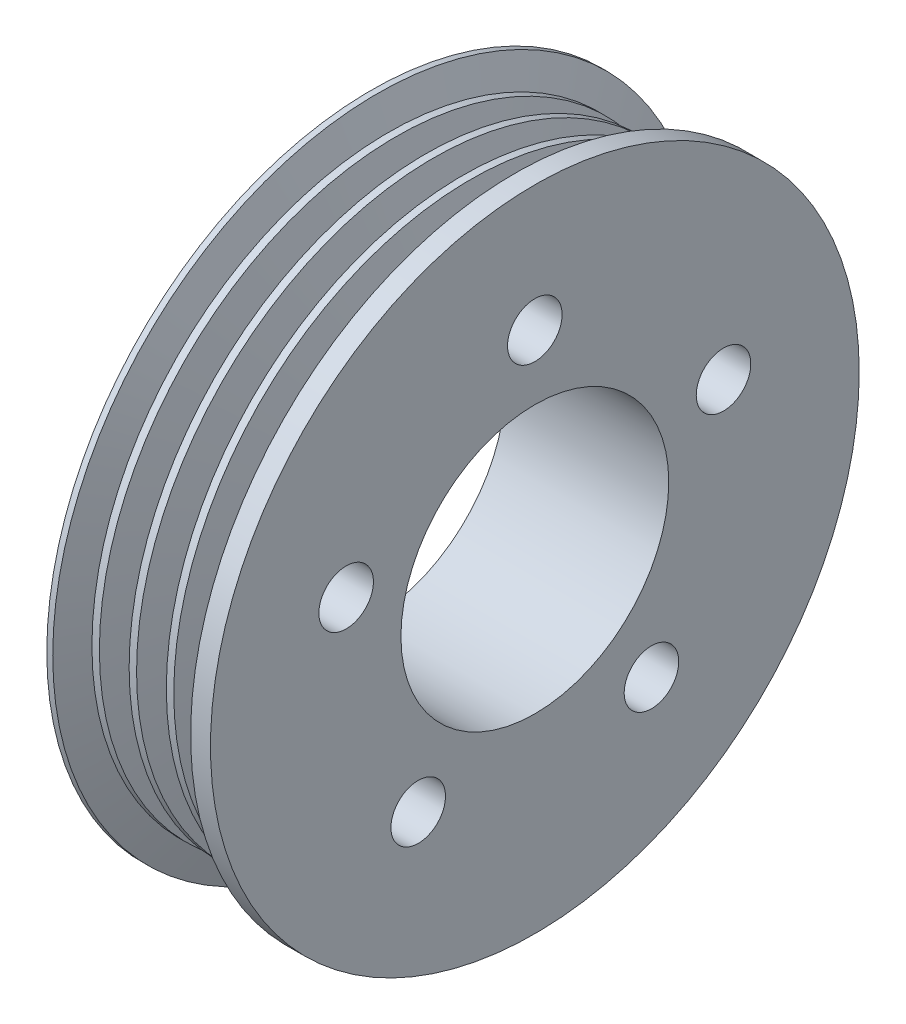
SolidWorks part; units mm, degrees
material "7075-O (SS)"
ref_plane "Plano frontal" through (0, 0, 0) normal (0, 0, 1) x (1, 0, 0)
ref_plane "Plano superior" through (0, 0, 0) normal (0, 1, 0) x (1, 0, 0)
ref_plane "Plano direito" through (0, 0, 0) normal (1, 0, 0) x (0, 0, -1)
sketch "Esboço1" plane through (0, 0, 0) normal (0, 0, 1) x (1, 0, 0)
  line L0 (0, 0) -> (14.25, 0) construction
  line L1 (0, 13.5) -> (16.5, 13.5)
  line L3 (16.5, 29.9) -> (13, 29.9)
  line L4 (13, 29.9) -> (11.9, 24.9)
  line L5 (11.9, 24.9) -> (11.1, 24.9)
  line L6 (11.1, 24.9) -> (10, 29.9)
  line L7 (10, 29.9) -> (9.25, 29.9)
  line L8 (9.25, 29.9) -> (8.15, 24.9)
  line L9 (8.15, 24.9) -> (7.35, 24.9)
  line L10 (7.35, 24.9) -> (6.25, 29.9)
  line L11 (6.25, 29.9) -> (5.5, 29.9)
  line L12 (5.5, 29.9) -> (4.4, 24.9)
  line L13 (4.4, 24.9) -> (3.6, 24.9)
  line L14 (3.6, 24.9) -> (2.5, 29.9)
  line L15 (2.5, 29.9) -> (0, 29.9)
  line L16 (0, 29.9) -> (0, 13.5)
  line L17 (16.5, 29.9) -> (16.5, 13.5)
  dimension "D1" = 0.75
  dimension "D2" = 16.4
  dimension "D3" = 2.5
  dimension "D4" = 0.8
  dimension "D5" = 5
  dimension "D6" = 13.5
  dimension "D8" = 3.5
revolve "Revolução1" add sketch "Esboço1" angle 360 about L0
hole_wizard "Escareado para parafuso com cabeça escareada elevada de M51" positions "Esboço2" profile "Esboço3" countersink size "M5" standard "ISO" end condition through all
sketch "Esboço2" plane through (0, 0, 0) normal (-1, 0, 0) x (0, 0, 1)
  line L0 (0, 0) -> (0, 20) construction
  point P0 (0, 20)
  dimension "D1" = 20
sketch "Esboço3" plane through (0, 20, 0) normal (0, 1, 0) x (0, 0, 1)
  line L0 (0, 0) -> (0, 16.5)
  line L1 (0, 16.5) -> (2.75, 16.5)
  line L2 (2.75, 16.5) -> (2.75, 2.45)
  line L3 (2.75, 2.45) -> (5.2, 0)
  line L5 (5.2, 0) -> (0, 0)
  line L6 (-2.75, 2.45) -> (-5.2, 0) construction
  line L11 (0, -6.35) -> (0, 107.95) construction
  dimension "Thru Hole Dia." = 5.5
  dimension "Thru Hole Depth" = 16.5
  dimension "Near C'Sink Dia." = 10.4
  dimension "Near C'Sink Angle" = 90
pattern_circular "PadrãoCircular1" count 5 over 360 about axis through (0, 0, 0) along (1, 0, 0) of "Escareado para parafuso com cabeça escareada elevada de M51"
sketch "Esboço4" plane through (0, 0, 0) normal (0, 0, 1) x (1, 0, 0)
  line L0 (0, 29.9) -> (0, 32.7)
  line L1 (0.6, 32.7) -> (1.75, 29.9)
  line L2 (1.75, 29.9) -> (0, 29.9)
  line L3 (0, 0) -> (16.5, 0) construction
  line L4 (16.5, -29.9) -> (16.5, 29.9) construction
  line L5 (0, 32.7) -> (0.6, 32.7)
  line L6 (2.5, 29.9) -> (2.5, -29.9) construction
  dimension "D1" = 2.8
  dimension "D2" = 0.6
  dimension "D3" = 0.75
revolve "Revolução2" add sketch "Esboço4" angle 360 about L3
sketch "Esboço5" plane through (16.5, 0, 0) normal (1, 0, 0) x (0, 0, -1)
  circle A0 centre (0, 0) radius 13.5 construction
  circle A1 centre (-11.7557, -16.1803) radius 2.75 construction
  circle A2 centre (11.7557, -16.1803) radius 2.75 construction
  circle A3 centre (19.0211, 6.1803) radius 2.75 construction
  circle A4 centre (0, 20) radius 2.75 construction
  circle A5 centre (-19.0211, 6.1803) radius 2.75 construction
  circle A6 centre (0, 0) radius 13.5
  circle A7 centre (-11.7557, -16.1803) radius 2.75
  circle A8 centre (11.7557, -16.1803) radius 2.75
  circle A9 centre (19.0211, 6.1803) radius 2.75
  circle A10 centre (0, 20) radius 2.75
  circle A11 centre (-19.0211, 6.1803) radius 2.75
  circle A12 centre (0, 0) radius 32.7
extrude "Ressalto-extrusão1" add sketch "Esboço5" against normal blind 2
